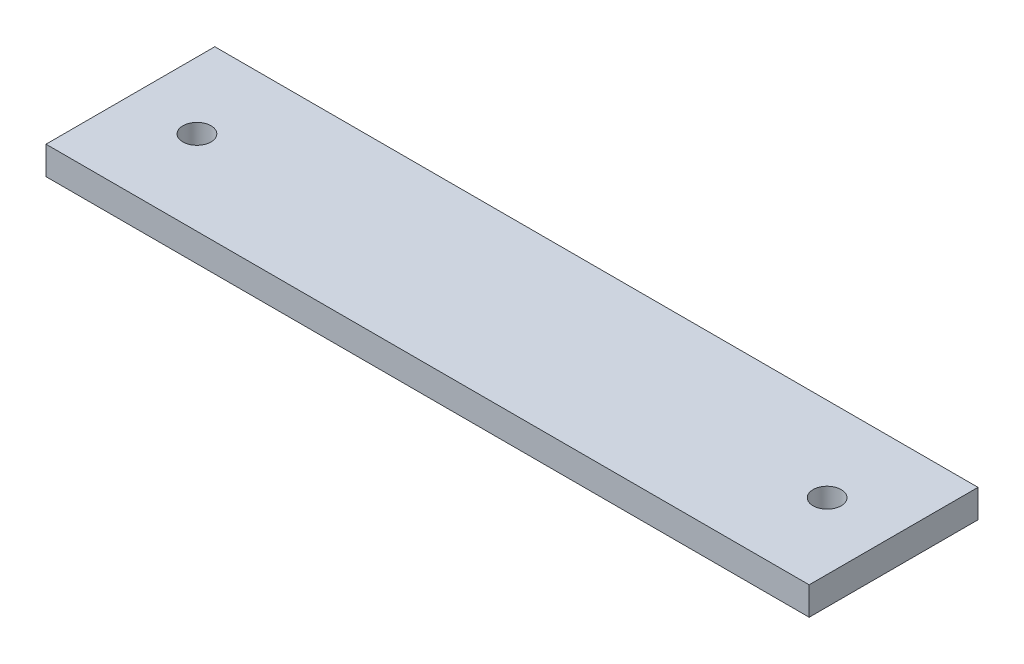
SolidWorks part; units mm, degrees
material "Plain Carbon Steel"
ref_plane "Front Plane" through (0, 0, 0) normal (0, 0, 1) x (1, 0, 0)
ref_plane "Top Plane" through (0, 0, 0) normal (0, 1, 0) x (1, 0, 0)
ref_plane "Right Plane" through (0, 0, 0) normal (1, 0, 0) x (0, 0, -1)
sketch "Sketch1" plane through (0, 0, 0) normal (0, 1, 0) x (1, 0, 0)
  line L1 (-86.12, 19.05) -> (86.12, 19.05)
  line L2 (-86.12, 19.05) -> (-86.12, -19.05)
  line L3 (-86.12, -19.05) -> (86.12, -19.05)
  line L4 (86.12, 19.05) -> (86.12, -19.05)
  line L5 (-86.12, 19.05) -> (86.12, -19.05) construction
  line L6 (-86.12, -19.05) -> (86.12, 19.05) construction
  point P0 (0, 0)
  dimension "D1" = 172.2399
  dimension "D2" = 38.1
extrude "Boss-Extrude1" add sketch "Sketch1" along normal blind 6.35
sketch "Sketch2" plane through (0, 0, 0) normal (0, -1, 0) x (1, 0, 0)
  line L0 (-86.12, -19.05) -> (-86.12, 19.05) construction
  line L1 (86.12, 19.05) -> (86.12, -19.05) construction
  line L2 (86.12, -19.05) -> (-86.12, -19.05) construction
  circle A0 centre (-71.1086, 0) radius 3.175
  circle A1 centre (71.12, 0) radius 3.175
  dimension "D1" = 15.0114
  dimension "D2" = 15
  dimension "D3" = 19.05
  dimension "D4" = 19.05
  dimension "D5" = 6.35
extrude "Cut-Extrude1" cut sketch "Sketch2" against normal up to next
